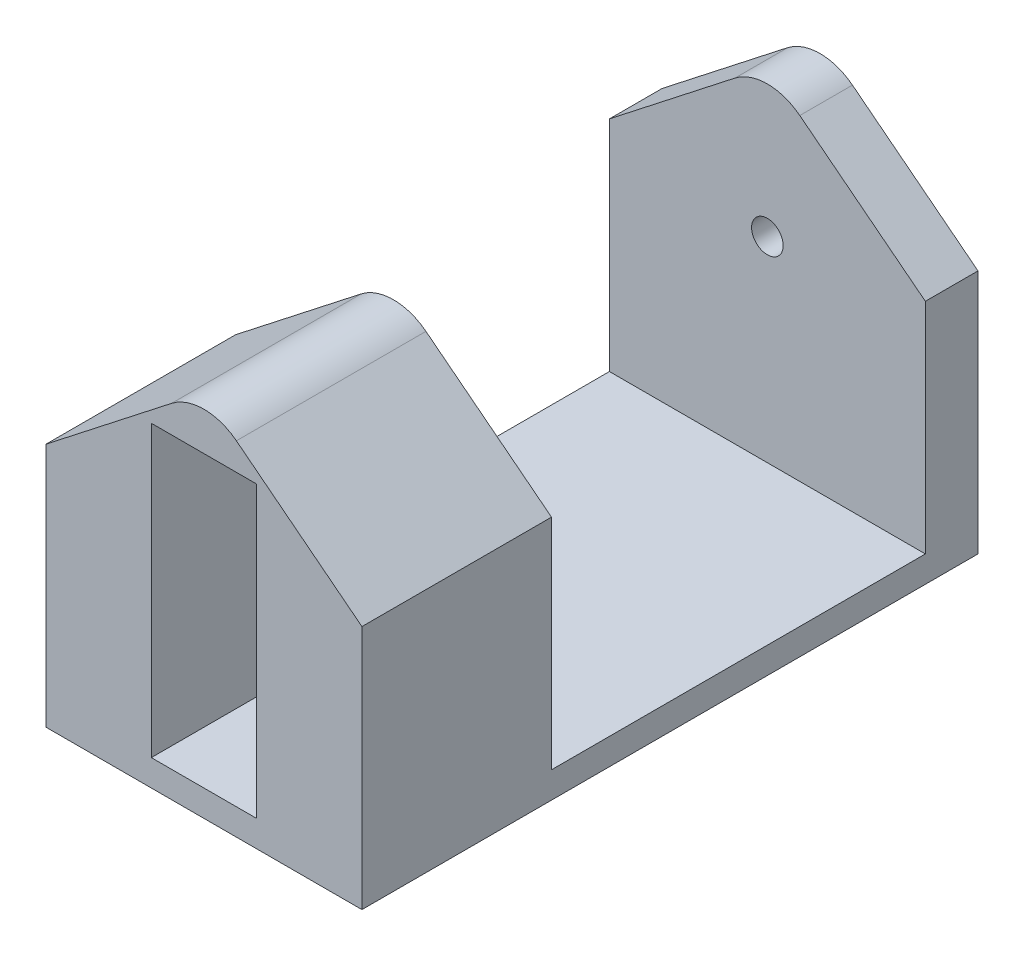
SolidWorks part; units mm, degrees
ref_plane "Front Plane" through (0, 0, 0) normal (0, 0, 1) x (1, 0, 0)
ref_plane "Top Plane" through (0, 0, 0) normal (0, 1, 0) x (1, 0, 0)
ref_plane "Right Plane" through (0, 0, 0) normal (1, 0, 0) x (0, 0, -1)
sketch "Sketch2" plane through (0, 0, 0) normal (0, 1, 0) x (1, 0, 0)
  line L1 (-40, 58.5) -> (40, 58.5)
  line L2 (-40, 58.5) -> (-40, -58.5)
  line L3 (-40, -58.5) -> (40, -58.5)
  line L4 (40, 58.5) -> (40, -58.5)
  line L5 (-40, 58.5) -> (40, -58.5) construction
  line L6 (-40, -58.5) -> (40, 58.5) construction
  point P0 (0, 0)
  dimension "D1" = 80
  dimension "D2" = 117
extrude "Boss-Extrude1" add sketch "Sketch2" along normal blind 70
sketch "Sketch3" plane through (0, 70, 0) normal (0, 1, 0) x (1, 0, 0)
  line L0 (-40, 48.5) -> (40, 48.5)
  line L1 (-40, 58.5) -> (-40, -58.5) construction
  line L2 (40, -58.5) -> (40, 58.5) construction
  line L3 (40, 58.5) -> (-40, 58.5) construction
  line L4 (-40, 48.5) -> (-40, -22.5)
  line L5 (-40, -22.5) -> (40, -22.5)
  line L6 (40, -22.5) -> (40, 48.5)
  dimension "D1" = 10
  dimension "D2" = 71
extrude "Cut-Extrude1" cut sketch "Sketch3" against normal blind 65
sketch "Sketch4" plane through (0, 0, 58.5) normal (0, 0, 1) x (1, 0, 0)
  line L0 (-40, 5) -> (40, 5) construction
  line L1 (-40, 70) -> (-40, 0) construction
  line L2 (40, 70) -> (40, 0) construction
  line L3 (-40, 0) -> (40, 0) construction
  line L4 (-10, 5) -> (10, 5)
  line L5 (-10, 5) -> (-10, 60)
  line L6 (-10, 60) -> (10, 60)
  line L7 (10, 60) -> (10, 5)
  point P10 (0, 5)
  dimension "D1" = 5
  dimension "D2" = 20
  dimension "D3" = 40
  dimension "D4" = 55
extrude "Cut-Extrude2" cut sketch "Sketch4" against normal blind 65
sketch "Sketch5" plane through (0, 0, 58.5) normal (0, 0, 1) x (1, 0, 0)
  line L0 (-6.1578, 65.1875) -> (-40, 38.739)
  line L1 (-40, 70) -> (40, 70) construction
  line L2 (-40, 70) -> (-40, 0) construction
  line L3 (6.1578, 65.1875) -> (40, 38.739)
  line L4 (40, 70) -> (40, 0) construction
  line L5 (-40, 38.739) -> (-40, 70)
  line L6 (-40, 70) -> (40, 70)
  line L7 (40, 70) -> (40, 38.739)
  arc A0 (-6.1578, 65.1875) -> (6.1578, 65.1875) centre (0, 57.3083) cw
  point P11 (0, 70)
  dimension "D1" = 10
extrude "Cut-Extrude3" cut sketch "Sketch5" against normal through all
sketch "Sketch6" plane through (0, 0, -48.5) normal (0, 0, 1) x (1, 0, 0)
  line L0 (0, 5) -> (0, 42.2) construction
  line L1 (-10, 5) -> (10, 5) construction
  circle A0 centre (0, 42.2) radius 3
  dimension "D1" = 37.2
extrude "Cut-Extrude4" cut sketch "Sketch6" against normal blind 65
ref_plane "Plane4" through (0, 67.3, 0) normal (0, 1, 0) x (1, 0, 0)
sketch "Sketch8" plane through (0, 67.3, 0) normal (0, 1, 0) x (1, 0, 0)
  line L0 (-40, 58.5) -> (-40, -58.5)
  line L1 (-40, -58.5) -> (-30, -58.5)
  line L2 (-40, -58.5) -> (-6.1578, -58.5) construction
  line L3 (-30, -58.5) -> (-30, 58.5)
  line L4 (-40, 58.5) -> (-6.1578, 58.5) construction
  line L5 (-30, 58.5) -> (-40, 58.5)
  line L6 (40, 58.5) -> (40, -58.5)
  line L7 (6.1578, -58.5) -> (40, -58.5) construction
  line L8 (40, -58.5) -> (30, -58.5)
  line L9 (30, -58.5) -> (30, 58.5)
  line L10 (6.1578, 58.5) -> (40, 58.5) construction
  line L11 (30, 58.5) -> (40, 58.5)
  dimension "D1" = 10
  dimension "D2" = 10
  dimension "D3" = 10
  dimension "D4" = 10
extrude "Cut-Extrude5" cut sketch "Sketch8" against normal through all
